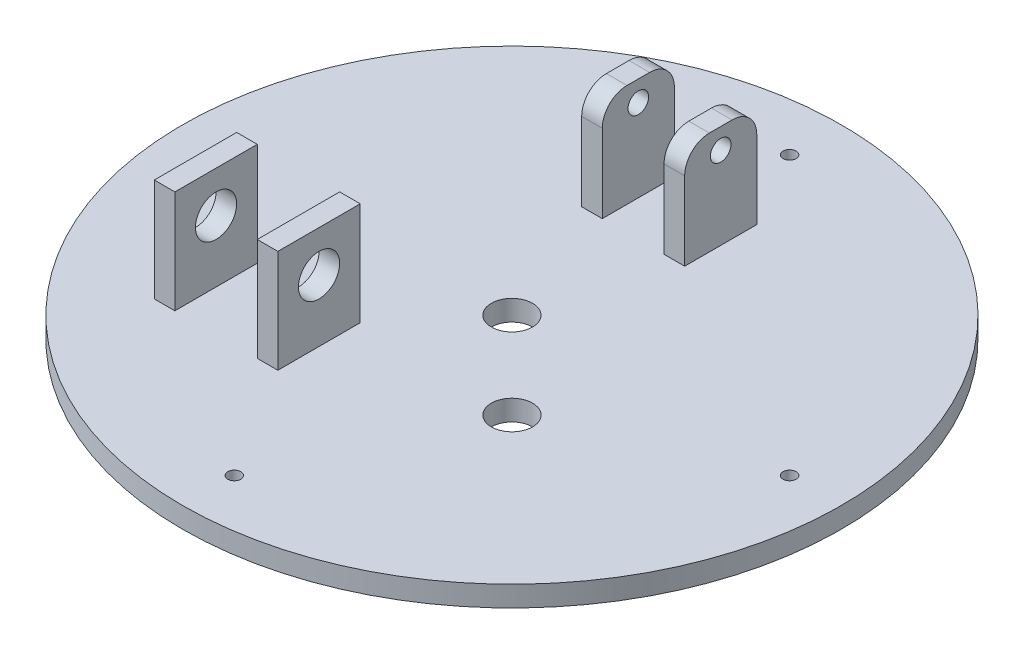
SolidWorks part; units mm, degrees
material "6061 Alloy"
ref_plane "Front Plane" through (0, 0, 0) normal (0, 0, 1) x (1, 0, 0)
ref_plane "Top Plane" through (0, 0, 0) normal (0, 1, 0) x (1, 0, 0)
ref_plane "Right Plane" through (0, 0, 0) normal (1, 0, 0) x (0, 0, -1)
sketch "Sketch1" plane through (0, 0, 0) normal (0, 1, 0) x (1, 0, 0)
  circle A0 centre (0, 0) radius 101.6
  dimension "D1" = 203.2
extrude "Boss-Extrude1" add sketch "Sketch1" along normal blind 6.35
sketch "Sketch2" plane through (0, 0, 0) normal (0, -1, 0) x (1, 0, 0)
  circle A0 centre (0, 0) radius 6.35
  dimension "D1" = 12.7
extrude "Cut-Extrude1" cut sketch "Sketch2" against normal through all
sketch "Sketch3" plane through (0, 6.35, 0) normal (0, 1, 0) x (1, 0, 0)
  line L0 (-53.1127, -38.1) -> (-27.7127, -38.1) construction
  line L1 (-59.4627, -25.4) -> (-53.1127, -25.4)
  line L2 (-59.4627, -25.4) -> (-59.4627, -50.8)
  line L3 (-59.4627, -50.8) -> (-53.1127, -50.8)
  line L4 (-53.1127, -25.4) -> (-53.1127, -50.8)
  line L5 (-27.7127, -25.4) -> (-21.3627, -25.4)
  line L6 (-27.7127, -25.4) -> (-27.7127, -50.8)
  line L7 (-27.7127, -50.8) -> (-21.3627, -50.8)
  line L8 (-21.3627, -25.4) -> (-21.3627, -50.8)
  point P10 (-40.4127, -38.1)
  dimension "D1" = 40.4127
  dimension "D2" = 6.35
  dimension "D3" = 38.1
  dimension "D4" = 25.4
  dimension "D5" = 25.4
extrude "Boss-Extrude2" add sketch "Sketch3" along normal blind 31.75
sketch "Sketch4" plane through (-21.3627, 0, 0) normal (1, 0, 0) x (0, 0, -1)
  line L0 (-38.1, 38.1) -> (-38.1, 25.4) construction
  line L1 (-50.8, 38.1) -> (-25.4, 38.1) construction
  circle A0 centre (-38.1, 25.4) radius 6.35
  dimension "D1" = 12.7
  dimension "D2" = 12.7
extrude "Cut-Extrude2" cut sketch "Sketch4" against normal up to surface (38.1 mm away) up to face at (-59.4627, 22.225, 38.1)
sketch "Sketch5" plane through (0, 6.35, 0) normal (0, 1, 0) x (1, 0, 0)
  line L0 (-11.8377, 50.8) -> (7.2123, 50.8) construction
  line L2 (-18.1877, 39.6875) -> (-11.8377, 39.6875)
  line L3 (-18.1877, 39.6875) -> (-18.1877, 61.9125)
  line L4 (-18.1877, 61.9125) -> (-11.8377, 61.9125)
  line L5 (-11.8377, 39.6875) -> (-11.8377, 61.9125)
  line L6 (7.2123, 61.9125) -> (13.5623, 61.9125)
  line L7 (7.2123, 61.9125) -> (7.2123, 39.6875)
  line L8 (7.2123, 39.6875) -> (13.5623, 39.6875)
  line L9 (13.5623, 61.9125) -> (13.5623, 39.6875)
  point P10 (-2.3127, 50.8)
  dimension "D1" = 22.225
  dimension "D2" = 6.35
  dimension "D3" = 19.05
  dimension "D4" = 38.1
  dimension "D5" = 88.9
extrude "Boss-Extrude3" add sketch "Sketch5" along normal blind 31.75
sketch "Sketch6" plane through (-18.1877, 0, 0) normal (-1, 0, 0) x (0, 0, 1)
  line L0 (-50.8, 38.1) -> (-50.8, 31.75) construction
  line L1 (-61.9125, 38.1) -> (-39.6875, 38.1) construction
  circle A0 centre (-50.8, 31.75) radius 3.175
  dimension "D1" = 6.35
  dimension "D2" = 6.35
extrude "Cut-Extrude3" cut sketch "Sketch6" against normal up to surface (31.75 mm away) up to face at (13.5623, 22.225, -50.8)
hole_wizard "#10-32 Tapped Hole1" positions "Sketch8" profile "Sketch7" tap size "#10-32" standard "ANSI Inch"
sketch "Sketch8" plane through (0, 0, 0) normal (0, -1, 0) x (-1, 0, 0)
  line L1 (85.5998, 0) -> (0, 85.5998)
  line L2 (85.5998, 0) -> (0, -85.5998)
  line L3 (0, 85.5998) -> (-85.5998, 0)
  line L4 (0, -85.5998) -> (-85.5998, 0)
  line L5 (85.5998, 0) -> (-85.5998, 0) construction
  line L6 (0, 85.5998) -> (0, -85.5998) construction
  point P252 (0, 0)
  point P331 (0, -85.5998)
  point P333 (-85.5998, 0)
  point P335 (0, 85.5998)
  point P337 (85.5998, 0)
  dimension "D1" = 121.0564
sketch "Sketch7" plane through (0, 0, 0) normal (1, 0, 0) x (0, 0, -1)
  line L0 (0, 0) -> (0, 13.2428)
  line L1 (0, 13.2428) -> (2.0193, 12.0294)
  line L2 (2.0193, 12.0294) -> (2.0193, 0)
  line L5 (2.0193, 0) -> (0, 0)
  line L10 (0, 13.2428) -> (-2.0193, 12.0294) construction
  line L11 (0, -6.35) -> (0, 107.95) construction
  dimension "Tap Drill Dia." = 4.0386
  dimension "Tap Drill Depth" = 12.0294
  dimension "Drill Angle" = 118
fillet "Fillet1" radius 7.62 4 edges at (10.3873, 38.1, -39.6875) (-15.0127, 38.1, -39.6875) (-15.0127, 38.1, -61.9125) (10.3873, 38.1, -61.9125)
sketch "Sketch9" plane through (0, 6.35, 0) normal (0, 1, 0) x (1, 0, 0)
  line L0 (0, 0) -> (71.842, -71.842) construction
  line L1 (0, 0) -> (26.6624, -26.6624) construction
  line L2 (85.5998, 0) -> (0, -85.5998)
  circle A0 centre (0, 0) radius 101.6 construction
  circle A1 centre (26.6624, -26.6624) radius 6.35
  point P11 (42.7999, -42.7999)
  dimension "D2" = 12.7
  dimension "D1" = 37.7063
ref_plane "Plane1" through (0, 6.35, 0) normal (0, 1, 0) x (1, 0, 0)
extrude "Cut-Extrude4" cut sketch "Sketch9" against normal through all contours A1
